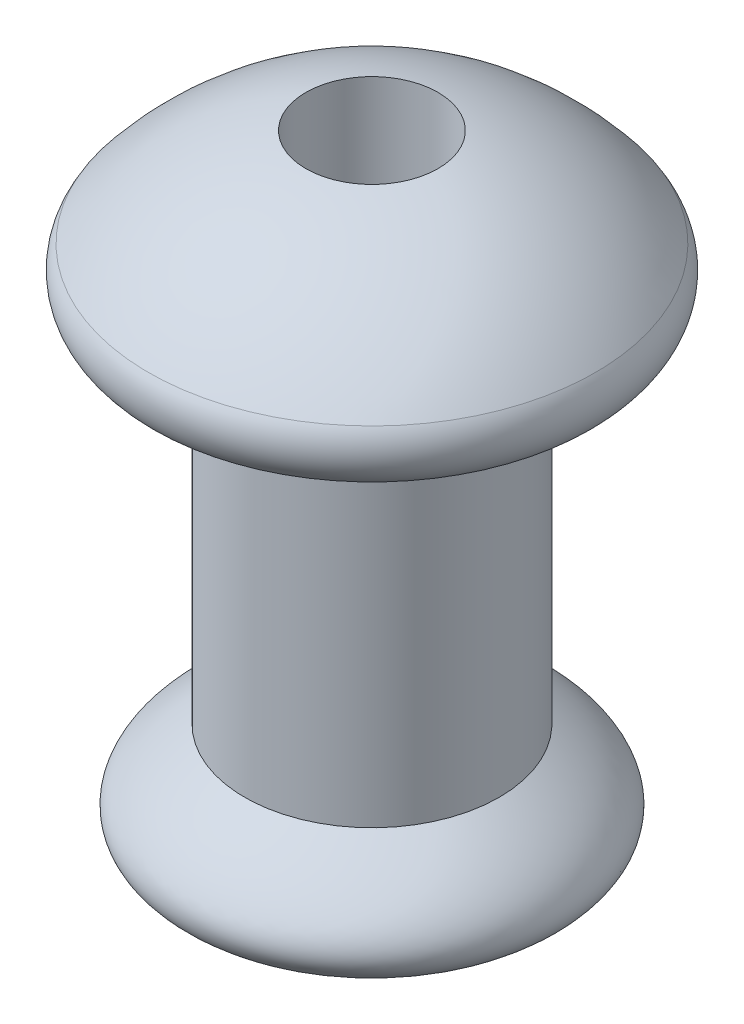
SolidWorks part; units mm, degrees
ref_plane "Front Plane" through (0, 0, 0) normal (0, 0, 1) x (1, 0, 0)
ref_plane "Top Plane" through (0, 0, 0) normal (0, 1, 0) x (1, 0, 0)
ref_plane "Right Plane" through (0, 0, 0) normal (1, 0, 0) x (0, 0, -1)
sketch "Sketch1" plane through (0, 0, 0) normal (0, 0, 1) x (1, 0, 0)
  line L0 (1.9015, -4.1879) -> (1.9015, 1.3121)
  line L1 (1.9015, 1.3121) -> (3.2708, 1.3121)
  line L2 (-0.0247, 3.6898) -> (-0.0247, -6.158)
  line L3 (-0.0247, -6.158) -> (0.3166, -6.158)
  line L4 (-0.0247, 0) -> (-0.0247, -11.6582) construction
  arc A0 (-0.0247, 3.6898) -> (3.3564, 2.1067) centre (0.0503, -0.5519) cw
  arc A1 (3.2708, 2.2097) -> (3.2708, 1.3121) centre (2.8352, 1.7609) cw
  spline S0 degree 3 poles (1.9015, -4.1879) (3.9978, -5.5054) (2.4014, -6.0037) (0.3166, -6.158) knots 0 0 0 0 1 1 1 1
revolve "Revolve1" add sketch "Sketch1" angle 360 about L4
sketch "Sketch2" plane through (0, -6.158, 0) normal (0, -1, 0) x (-1, 0, 0)
  circle A0 centre (0.0247, 0) radius 1
extrude "Cut-Extrude2" cut sketch "Sketch2" against normal through all contours A0
